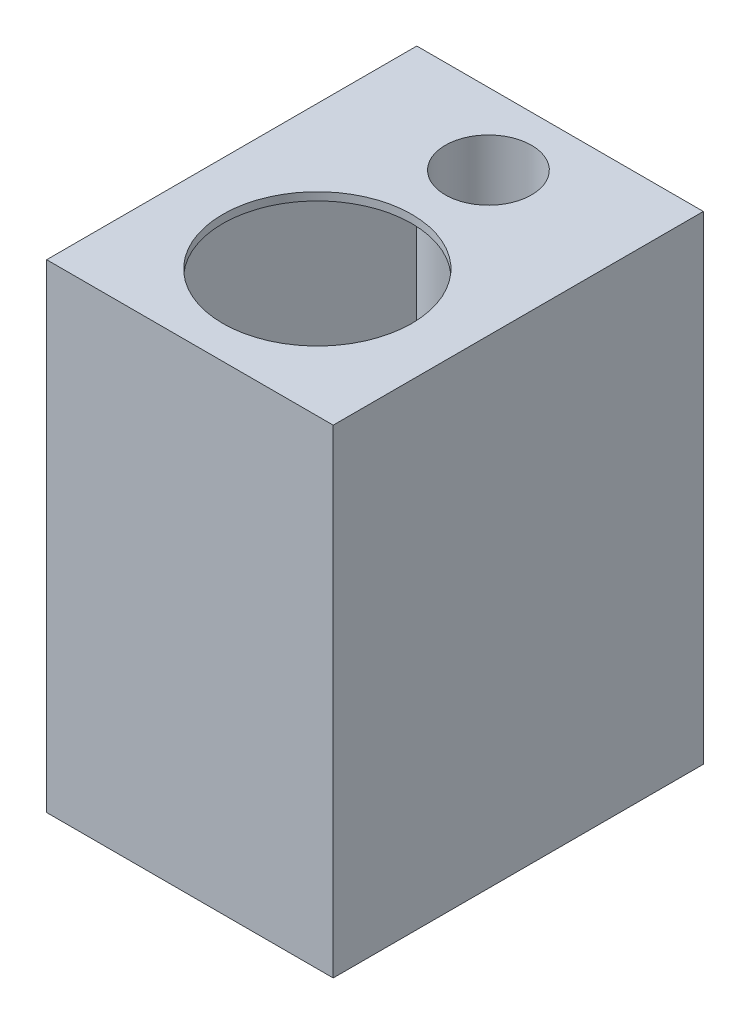
SolidWorks part; units mm, degrees
ref_plane "Front" through (0, 0, 0) normal (0, 0, 1) x (1, 0, 0)
ref_plane "Top" through (0, 0, 0) normal (0, 1, 0) x (1, 0, 0)
ref_plane "Right" through (0, 0, 0) normal (1, 0, 0) x (0, 0, -1)
sketch "Sketch2" plane through (0, 0, 0) normal (0, 1, 0) x (1, 0, 0)
  line L1 (0, 0) -> (144, 0)
  line L2 (0, 0) -> (0, 186)
  line L3 (0, 186) -> (144, 186)
  line L4 (144, 0) -> (144, 186)
  dimension "D1" = 144
  dimension "D2" = 186
extrude "Boss-Extrude1" add sketch "Sketch2" along normal blind 4
sketch "Sketch3" plane through (0, 0, 0) normal (0, -1, 0) x (-1, 0, 0)
  line L0 (-4, 4) -> (-4, 182)
  line L1 (0, 0) -> (-144, 0)
  line L2 (0, 0) -> (0, 186)
  line L3 (0, 186) -> (-144, 186)
  line L4 (-144, 0) -> (-144, 186)
  line L5 (-4, 182) -> (-140, 182)
  line L6 (-140, 4) -> (-140, 182)
  line L7 (-4, 4) -> (-140, 4)
  dimension "D1" = 4
extrude "Boss-Extrude2" add sketch "Sketch3" along normal blind 236.6
sketch "Sketch4" plane through (0, 4, 0) normal (0, 1, 0) x (1, 0, 0)
  line L0 (0, 186) -> (0, 0) construction
  line L1 (0, 0) -> (144, 0) construction
  circle A0 centre (72, 64) radius 47.5
  point P4 (0, 0)
  dimension "D1" = 95
  dimension "D2" = 72
  dimension "D3" = 64
extrude "Cut-Extrude1" cut sketch "Sketch4" against normal blind 4
sketch "Sketch5" plane through (0, 0, 0) normal (0, -1, 0) x (-1, 0, 0)
  line L0 (-4, 182) -> (-140, 182) construction
  line L1 (-4, 4) -> (-4, 182) construction
  circle A0 centre (-72, 150) radius 21.65
  dimension "D1" = 43.3
  dimension "D2" = 32
  dimension "D3" = 68
extrude "Cut-Extrude2" cut sketch "Sketch5" against normal blind 4
sketch "Sketch6" plane through (0, 0, 0) normal (0, -1, 0) x (-1, 0, 0)
  circle A0 centre (-72, 150) radius 21.65
  circle A1 centre (-72, 150) radius 25.65
  dimension "D1" = 4
extrude "Boss-Extrude3" add sketch "Sketch6" along normal blind 103.7
equation "\"D2@Sketch2\"=140*1.3+4"
equation "\"D1@Sketch2\"=140+4"
equation "\"D1@Boss-Extrude2\"=140*1.3*1.3"
equation "\"D2@Sketch4\"=\"D1@Sketch2\"/2"
equation "\"D3@Sketch4\"=\"D2@Sketch4\"-8"
equation "\"D3@Sketch5\"=\"D1@Sketch2\"/2-4"
